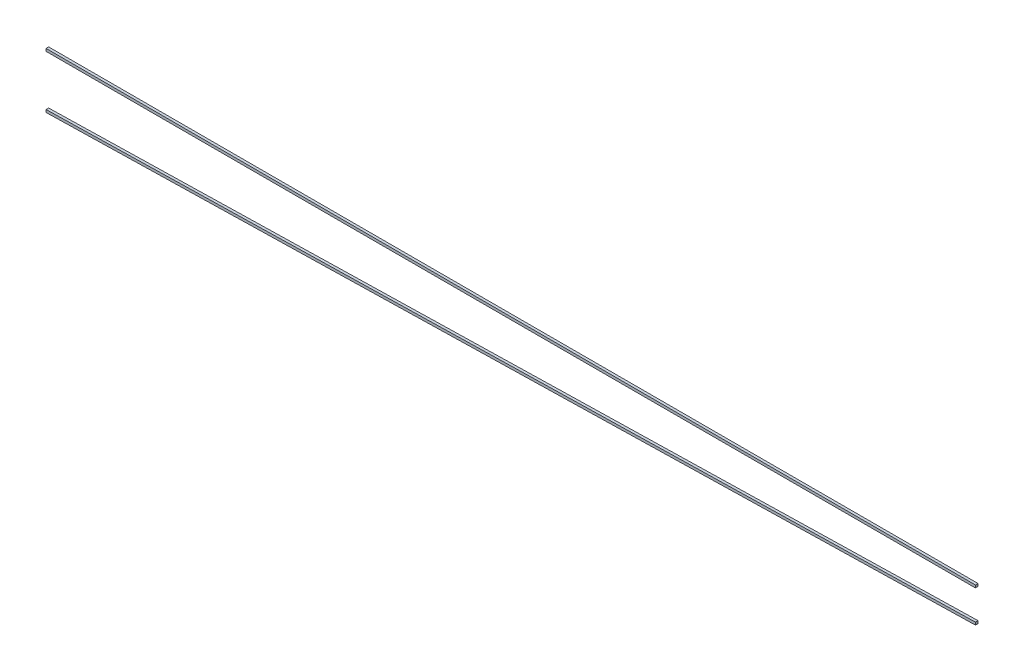
SolidWorks part; units mm, degrees
ref_plane "前视基准面" through (0, 0, 0) normal (0, 0, 1) x (1, 0, 0)
ref_plane "上视基准面" through (0, 0, 0) normal (0, 1, 0) x (1, 0, 0)
ref_plane "右视基准面" through (0, 0, 0) normal (1, 0, 0) x (0, 0, -1)
sketch "Model" plane through (0, 0, 0) normal (0, 0, 1) x (1, 0, 0)
  line L0 (607.6456, 355.9686) -> (643.4203, 355.9686)
  line L1 (607.6456, 313.1208) -> (643.4203, 313.9194)
  line L2 (643.4203, 355.9686) -> (745.3354, 355.9686)
  line L3 (745.3354, 355.9686) -> (890.239, 355.9686)
  line L4 (890.239, 355.9686) -> (1053.0164, 355.9686)
  line L5 (1053.0164, 355.9686) -> (1216.5745, 355.9686)
  line L6 (1216.5745, 355.9686) -> (1324.8772, 355.9686)
  line L7 (643.4203, 313.9194) -> (745.3354, 316.1946)
  line L8 (745.3354, 316.1946) -> (890.239, 319.4293)
  line L9 (890.239, 319.4293) -> (1053.0164, 323.0631)
  line L10 (1053.0164, 323.0631) -> (1216.5745, 326.7143)
  line L11 (1216.5745, 326.7143) -> (1324.8772, 329.1321)
  line L12 (607.6456, 353.9686) -> (1324.8772, 353.9686)
  line L13 (1324.8772, 331.1321) -> (607.601, 315.1203)
  line L14 (607.6456, 355.9686) -> (607.6456, 353.9686)
  line L15 (607.601, 315.1203) -> (607.6456, 313.1208)
  line L16 (1324.8772, 355.9686) -> (1324.8772, 353.9686)
  line L17 (1324.8772, 331.1321) -> (1324.8772, 329.1321)
extrude "凸台-拉伸1" add sketch "Model" along normal blind 2
